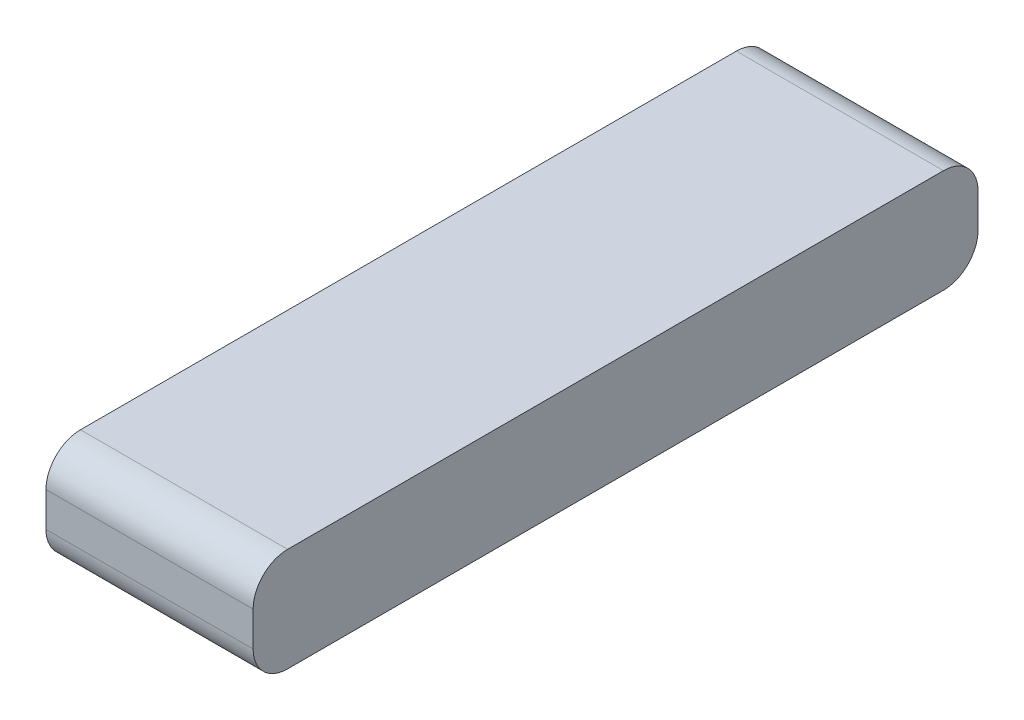
SolidWorks part; units mm, degrees
ref_plane "Front Plane" through (0, 0, 0) normal (0, 0, 1) x (1, 0, 0)
ref_plane "Top Plane" through (0, 0, 0) normal (0, 1, 0) x (1, 0, 0)
ref_plane "Right Plane" through (0, 0, 0) normal (1, 0, 0) x (0, 0, -1)
sketch "Sketch1" plane through (0, 0, 0) normal (0, 1, 0) x (1, 0, 0)
  line L1 (0, 0) -> (38.1, 0)
  line L2 (0, 0) -> (0, 133.35)
  line L3 (0, 133.35) -> (38.1, 133.35)
  line L4 (38.1, 0) -> (38.1, 133.35)
  dimension "D1" = 133.35
  dimension "D2" = 38.1
extrude "Boss-Extrude1" add sketch "Sketch1" along normal blind 19.05
fillet "Fillet1" radius 6.35 4 edges at (19.05, 0, -133.35) (19.05, 19.05, -133.35) (19.05, 0, 0) (19.05, 19.05, 0)
